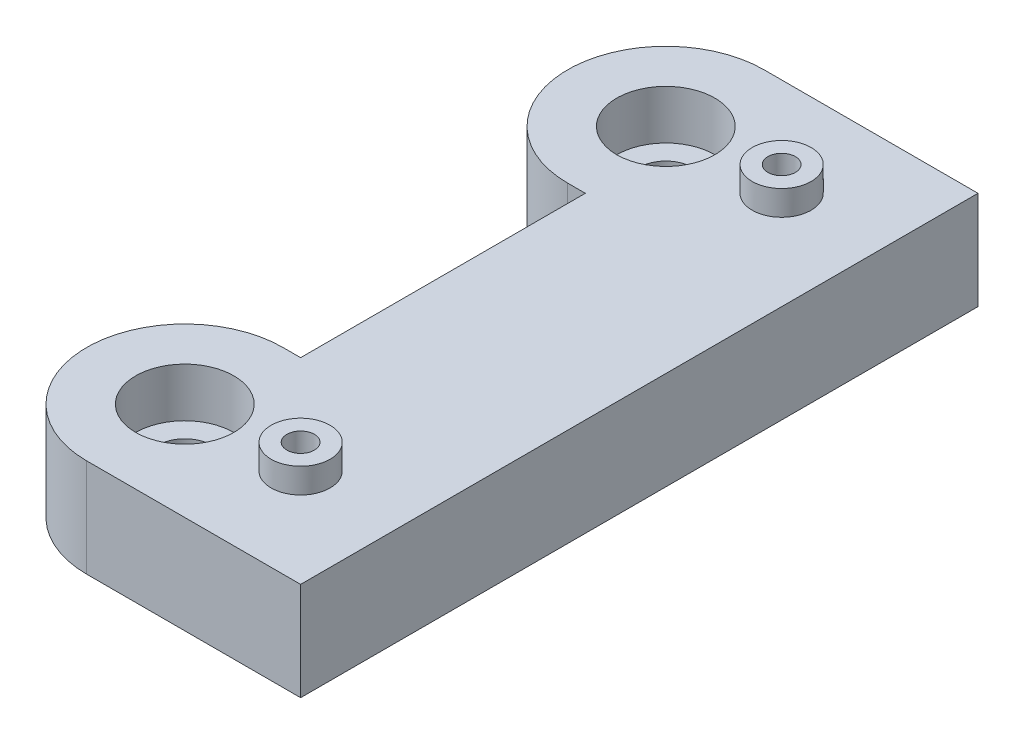
SolidWorks part; units mm, degrees
ref_plane "Front Plane" through (0, 0, 0) normal (0, 0, 1) x (1, 0, 0)
ref_plane "Top Plane" through (0, 0, 0) normal (0, 1, 0) x (1, 0, 0)
ref_plane "Right Plane" through (0, 0, 0) normal (1, 0, 0) x (0, 0, -1)
sketch "Sketch1" plane through (0, 0, 0) normal (0, 1, 0) x (1, 0, 0)
  line L1 (-29, 24.5) -> (29, 24.5)
  line L2 (-29, 24.5) -> (-29, -24.5)
  line L3 (-29, -24.5) -> (29, -24.5)
  line L4 (29, 24.5) -> (29, -24.5)
  line L5 (-29, 24.5) -> (29, -24.5) construction
  line L6 (-29, -24.5) -> (29, 24.5) construction
  line L7 (-50.8, 39.5) -> (50.8, 39.5)
  line L8 (-50.8, 39.5) -> (-50.8, -39.5)
  line L9 (-50.8, -39.5) -> (50.8, -39.5)
  line L10 (50.8, 39.5) -> (50.8, -39.5)
  line L11 (-50.8, 39.5) -> (50.8, -39.5) construction
  line L12 (-50.8, -39.5) -> (50.8, 39.5) construction
  point P0 (0, 0)
  point P6 (0, 0)
  dimension "D1" = 58
  dimension "D2" = 49
  dimension "D3" = 101.6
  dimension "D4" = 15
sketch "Sketch2" plane through (0, 0, 0) normal (0, 1, 0) x (1, 0, 0)
  line L0 (-40.8, 24.5) -> (-29, 24.5) construction
  line L1 (-29, 24.5) -> (-29, -24.5) construction
  line L2 (-29, -24.5) -> (-40.8, -24.5) construction
  line L3 (-40.8, 14.5) -> (-39, 14.5)
  line L4 (-39, 14.5) -> (-39, -14.5)
  line L5 (-39, -14.5) -> (-40.8, -14.5)
  line L6 (-40.8, 34.5) -> (-19, 34.5)
  line L7 (-19, 34.5) -> (-19, -34.5)
  line L8 (-19, -34.5) -> (-40.8, -34.5)
  line L9 (-50.8, 39.5) -> (-50.8, -39.5) construction
  circle A0 centre (-29, -24.5) radius 1.4
  circle A1 centre (-29, 24.5) radius 1.4
  arc A2 (-40.8, 14.5) -> (-40.8, 34.5) centre (-40.8, 24.5) cw
  arc A3 (-40.8, -14.5) -> (-40.8, -34.5) centre (-40.8, -24.5) ccw
  point P18 (-41.7339, -24.5)
  point P19 (-45.4851, 25.9017)
  point P22 (0, 0)
  dimension "D1" = 2.8
  dimension "D2" = 10
  dimension "D4" = 10
  dimension "D3" = 10
extrude "Boss-Extrude1" add sketch "Sketch2" along normal blind 10
sketch "Sketch3" plane through (0, 10, 0) normal (0, 1, 0) x (1, 0, 0)
  circle A0 centre (-29, 24.5) radius 3
  circle A1 centre (-29, -24.5) radius 3
  circle A2 centre (-29, 24.5) radius 1.4 construction
  circle A3 centre (-29, -24.5) radius 1.4 construction
  circle A4 centre (-29, 24.5) radius 1.4
  circle A5 centre (-29, -24.5) radius 1.4
  dimension "D1" = 6
extrude "Boss-Extrude2" add sketch "Sketch3" along normal blind 2.54
hole_wizard "CBORE for M5 SHCS1" positions "Sketch4" profile "Sketch5" counterbore size "M5" standard "ANSI Metric"
sketch "Sketch4" plane through (0, 10, 0) normal (0, 1, 0) x (1, 0, 0)
  arc A0 (-40.8, 34.5) -> (-40.8, 14.5) centre (-40.8, 24.5) ccw construction
  arc A1 (-40.8, -14.5) -> (-40.8, -34.5) centre (-40.8, -24.5) ccw construction
  point P0 (-40.8, -24.5)
  point P2 (-40.8, 24.5)
  point P5 (0, 0)
  point P12 (0, 0)
sketch "Sketch5" plane through (-40.8, 10, 24.5) normal (1, 0, 0) x (0, 0, 1)
  line L0 (0, 0) -> (0, 13.6524)
  line L1 (0, 13.6524) -> (2.75, 12)
  line L2 (2.75, 12) -> (2.75, 5)
  line L3 (2.75, 5) -> (5, 5)
  line L4 (5, 5) -> (5, 0)
  line L5 (5, 0) -> (0, 0)
  line L10 (0, 13.6524) -> (-2.75, 12) construction
  line L11 (0, -6.35) -> (0, 107.95) construction
  dimension "Hole Dia." = 5.5
  dimension "Hole Depth" = 12
  dimension "C'Bore Dia." = 10
  dimension "C'Bore Depth" = 5
  dimension "Drill Angle" = 118
